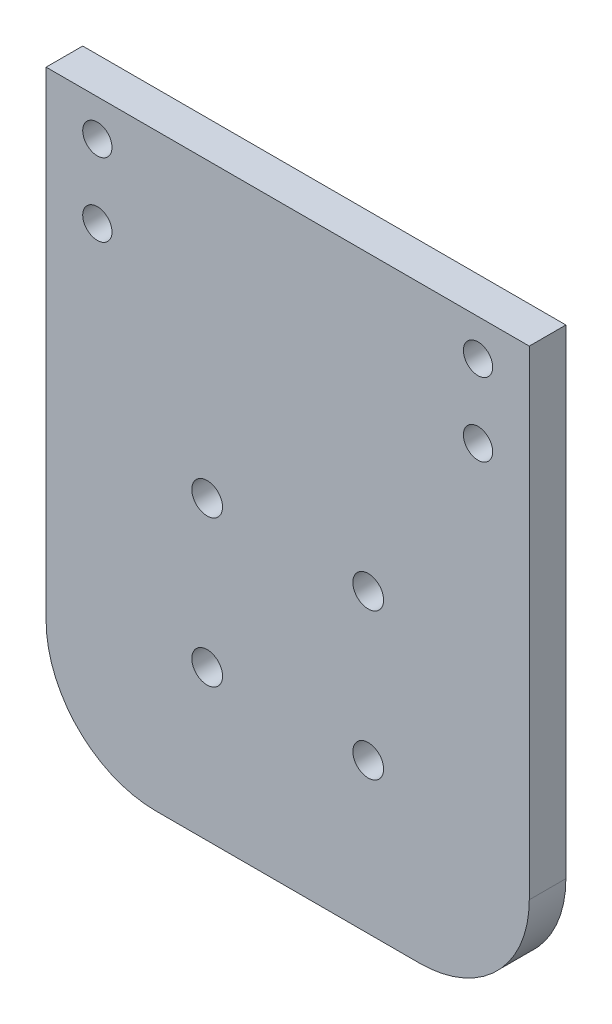
SolidWorks part; units mm, degrees
ref_plane "前视基准面" through (0, 0, 0) normal (0, 0, 1) x (1, 0, 0)
ref_plane "上视基准面" through (0, 0, 0) normal (0, 1, 0) x (1, 0, 0)
ref_plane "右视基准面" through (0, 0, 0) normal (1, 0, 0) x (0, 0, -1)
sketch "草图1" plane through (0, 0, 0) normal (0, 0, 1) x (1, 0, 0)
  line L1 (33, -40.25) -> (-33, -40.25)
  line L2 (33, -40.25) -> (33, 40.25)
  line L3 (33, 40.25) -> (-33, 40.25)
  line L4 (-33, -40.25) -> (-33, 40.25)
  line L5 (33, -40.25) -> (-33, 40.25) construction
  line L6 (33, 40.25) -> (-33, -40.25) construction
  point P0 (0, 0)
  dimension "D1" = 80.5
  dimension "D2" = 66
extrude "凸台-拉伸1" add sketch "草图1" along normal blind 5
sketch "草图2" plane through (0, 0, 5) normal (0, 0, 1) x (1, 0, 0)
  line L0 (33, 40.25) -> (-33, 40.25) construction
  line L1 (-33, 40.25) -> (-33, -40.25) construction
  line L2 (33, -40.25) -> (33, 40.25) construction
  circle A0 centre (-26, 35.25) radius 2
  circle A1 centre (26, 35.25) radius 2
  circle A2 centre (26, 25.25) radius 2
  circle A3 centre (-26, 25.25) radius 2
  dimension "D1" = 10
  dimension "D2" = 10
  dimension "D3" = 5
  dimension "D4" = 5
  dimension "D5" = 7
  dimension "D6" = 7
  dimension "D7" = 7
  dimension "D8" = 7
  dimension "D9" = 4
  dimension "D10" = 4
  dimension "D11" = 4
  dimension "D12" = 4
extrude "切除-拉伸1" cut sketch "草图2" against normal through all
sketch "草图3" plane through (0, 0, 5) normal (0, 0, 1) x (1, 0, 0)
  line L0 (33, 40.25) -> (-33, 40.25) construction
  circle A0 centre (-11, 0.25) radius 2.1
  circle A1 centre (11, 0.25) radius 2.1
  circle A2 centre (11, -19.75) radius 2.1
  circle A3 centre (-11, -19.75) radius 2.1
  dimension "D1" = 40
  dimension "D2" = 40
  dimension "D3" = 22
  dimension "D4" = 22
  dimension "D5" = 11
  dimension "D6" = 11
  dimension "D7" = 4.2
  dimension "D8" = 4.2
  dimension "D9" = 4.2
  dimension "D10" = 4.2
  dimension "D11" = 20
  dimension "D12" = 20
extrude "切除-拉伸2" cut sketch "草图3" against normal blind 10
fillet "圆角1" radius 15 2 edges at (-33, -40.25, 2.5) (33, -40.25, 2.5)
